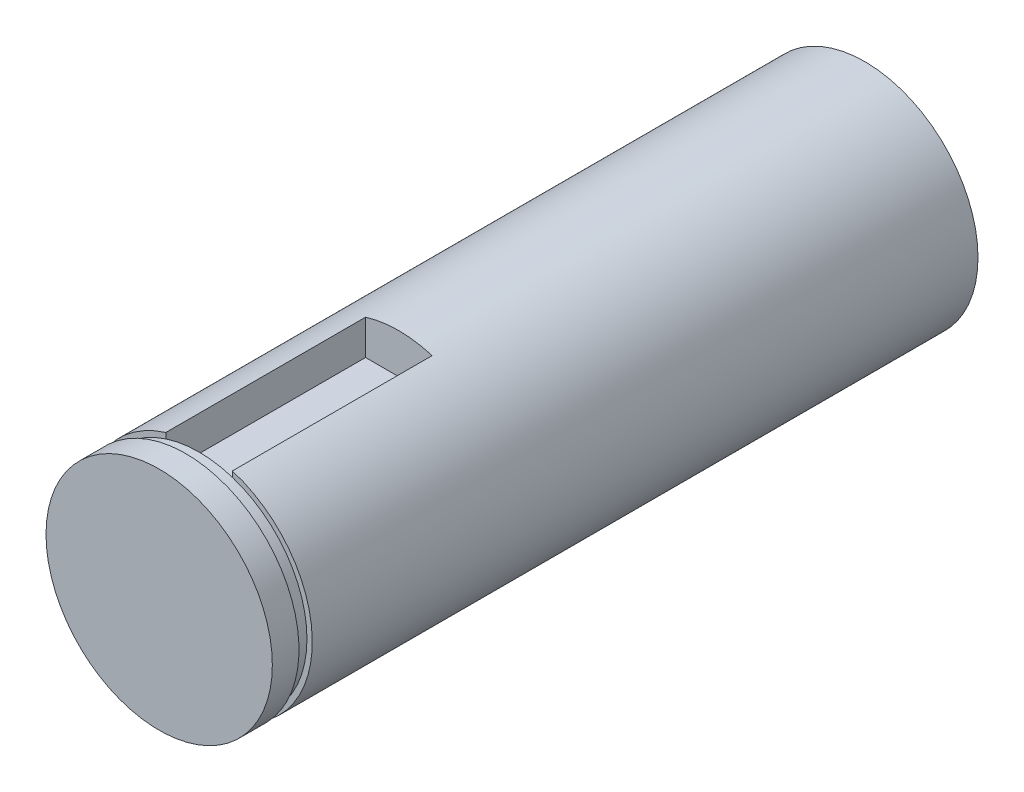
SolidWorks part; units mm, degrees
ref_plane "Front Plane" through (0, 0, 0) normal (0, 0, 1) x (1, 0, 0)
ref_plane "Top Plane" through (0, 0, 0) normal (0, 1, 0) x (1, 0, 0)
ref_plane "Right Plane" through (0, 0, 0) normal (1, 0, 0) x (0, 0, -1)
sketch "Sketch1" plane through (0, 0, 0) normal (0, 0, 1) x (1, 0, 0)
  circle A0 centre (0, 0) radius 8.5
  dimension "D1" = 17
extrude "Boss-Extrude1" add sketch "Sketch1" along normal blind 50
sketch "Sketch2" plane through (0, 0, 50) normal (0, 0, 1) x (1, 0, 0)
  line L1 (-2.5, 8.5) -> (2.5, 8.5)
  line L2 (-2.5, 8.5) -> (-2.5, 5.5)
  line L3 (-2.5, 5.5) -> (2.5, 5.5)
  line L4 (2.5, 8.5) -> (2.5, 5.5)
  circle A1 centre (0, 0) radius 8.5 construction
  point P4 (0, 8.5)
  point P6 (0, 5.5)
  dimension "D1" = 3
  dimension "D2" = 5
extrude "Cut-Extrude1" cut sketch "Sketch2" against normal blind 15
sketch "Sketch3" plane through (0, 0, 50) normal (0, 0, 1) x (1, 0, 0)
  circle A0 centre (0, 0) radius 8.5
  dimension "D1" = 17
extrude "Boss-Extrude2" add sketch "Sketch3" along normal blind 3
sketch "Sketch4" plane through (0, 0, 50) normal (0, 0, -1) x (-1, 0, 0)
  circle A0 centre (0, 0) radius 9
  circle A1 centre (0, 0) radius 8.1
  dimension "D1" = 16.2
  dimension "D2" = 18
extrude "Cut-Extrude2" cut sketch "Sketch4" against normal blind 1
